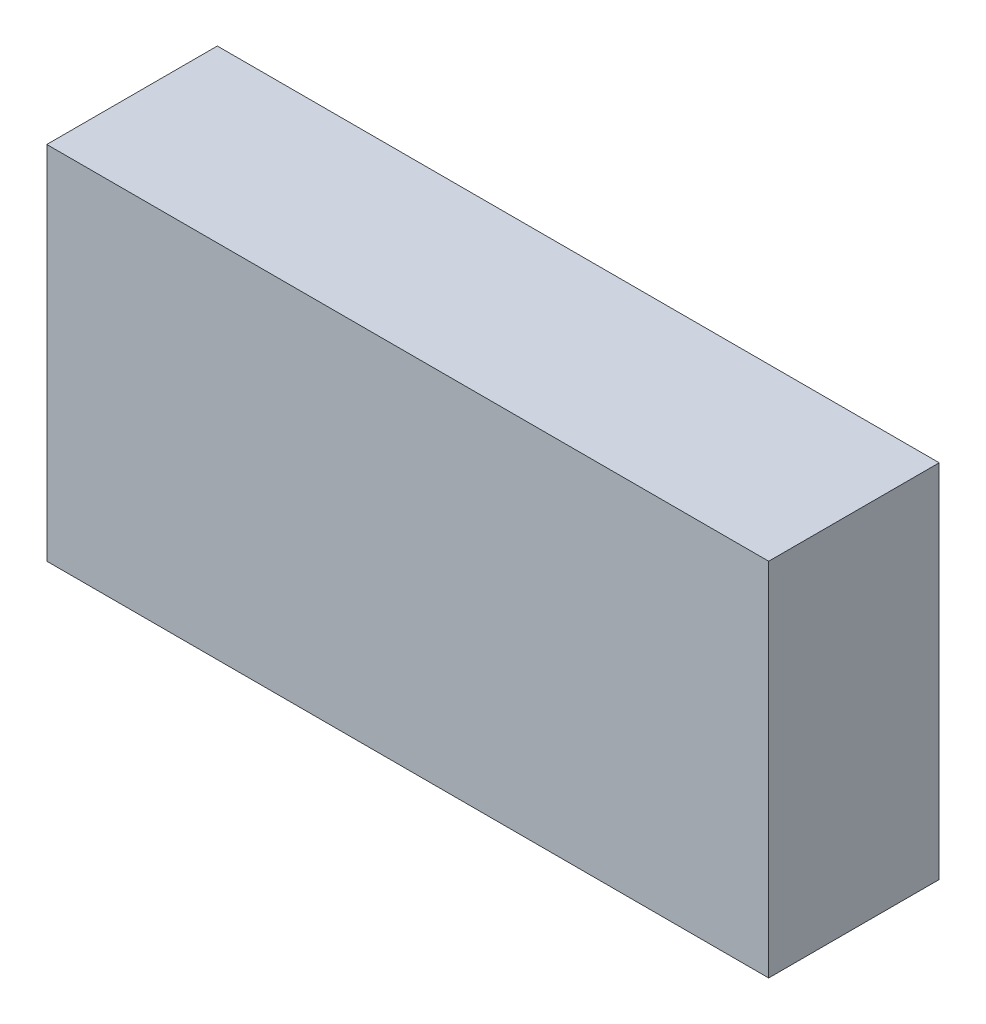
SolidWorks part; units mm, degrees
material "Acrílico TEC"
ref_plane "Alzado" through (0, 0, 0) normal (0, 0, 1) x (1, 0, 0)
ref_plane "Planta" through (0, 0, 0) normal (0, 1, 0) x (1, 0, 0)
ref_plane "Vista lateral" through (0, 0, 0) normal (1, 0, 0) x (0, 0, -1)
sketch "Croquis1" plane through (0, 0, 0) normal (0, 0, 1) x (1, 0, 0)
  line L1 (0, 0) -> (25.4, 0)
  line L2 (0, 0) -> (0, 12.7)
  line L3 (0, 12.7) -> (25.4, 12.7)
  line L4 (25.4, 0) -> (25.4, 12.7)
  dimension "D1" = 25.4
  dimension "D2" = 12.7
extrude "Saliente-Extruir1" add sketch "Croquis1" along normal blind 6
